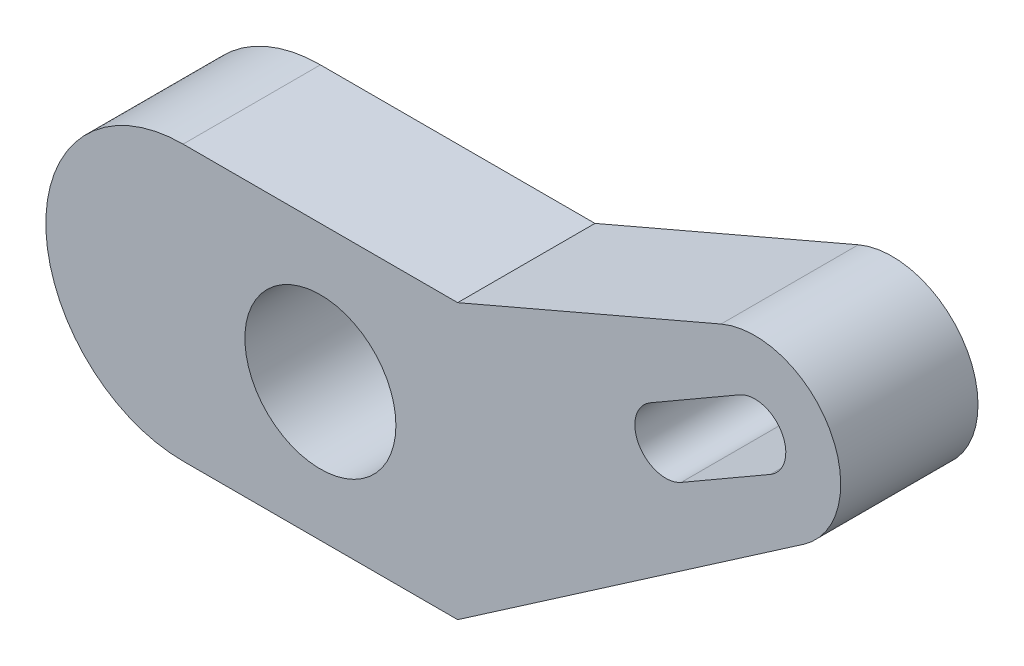
SolidWorks part; units mm, degrees
ref_plane "Спереди" through (0, 0, 0) normal (0, 0, 1) x (1, 0, 0)
ref_plane "Сверху" through (0, 0, 0) normal (0, 1, 0) x (1, 0, 0)
ref_plane "Справа" through (0, 0, 0) normal (1, 0, 0) x (0, 0, -1)
sketch "Эскиз1" plane through (0, 0, 0) normal (0, 0, 1) x (1, 0, 0)
  line L0 (0, 0) -> (40, 0) construction
  line L1 (0, 20) -> (40, 20)
  line L2 (0, -20) -> (40, -20)
  line L3 (40, 20) -> (40, -20)
  arc A0 (0, 20) -> (0, -20) centre (0, 0) ccw
  arc A1 (40, -20) -> (40, 20) centre (40, 0) ccw
  point P3 (20, 0)
  dimension "D1" = 40
  dimension "D2" = 40
extrude "Бобышка-Вытянуть1" add sketch "Эскиз1" along normal blind 20
sketch "Эскиз2" plane through (0, 0, 0) normal (0, 0, 1) x (1, 0, 0)
  line L0 (40, 0) -> (83.3013, 25) construction
  line L1 (40, 20) -> (40, -20) construction
  line L2 (40, 0) -> (78.5579, 0) construction
  line L3 (78.3667, 36.4848) -> (40, 20)
  line L4 (40, -20) -> (90.3914, 14.7053)
  line L5 (40, 20) -> (40, -20)
  circle A0 centre (83.3013, 25) radius 12.5
  dimension "D1" = 30
  dimension "D2" = 25
  dimension "D3" = 50
extrude "Бобышка-Вытянуть2" add sketch "Эскиз2" along normal blind 20 contours A0 L3 L5 L4 | A0
sketch "Эскиз3" plane through (0, 0, 20) normal (0, 0, 1) x (1, 0, 0)
  line L0 (0, 0) -> (40, 0) construction
  line L1 (40, 0) -> (40, 20) construction
  line L2 (81.0513, 28.8971) -> (68.0609, 21.3971)
  line L4 (72.5609, 13.6029) -> (85.5513, 21.1029)
  line L5 (40, 0) -> (83.3013, 25) construction
  circle A0 centre (20, 0) radius 11
  circle A1 centre (83.3013, 25) radius 4.5
  circle A2 centre (70.3109, 17.5) radius 4.5
  dimension "D1" = 22
  dimension "D2" = 9
  dimension "D3" = 15
extrude "Вырез-Вытянуть1" cut sketch "Эскиз3" against normal through all
